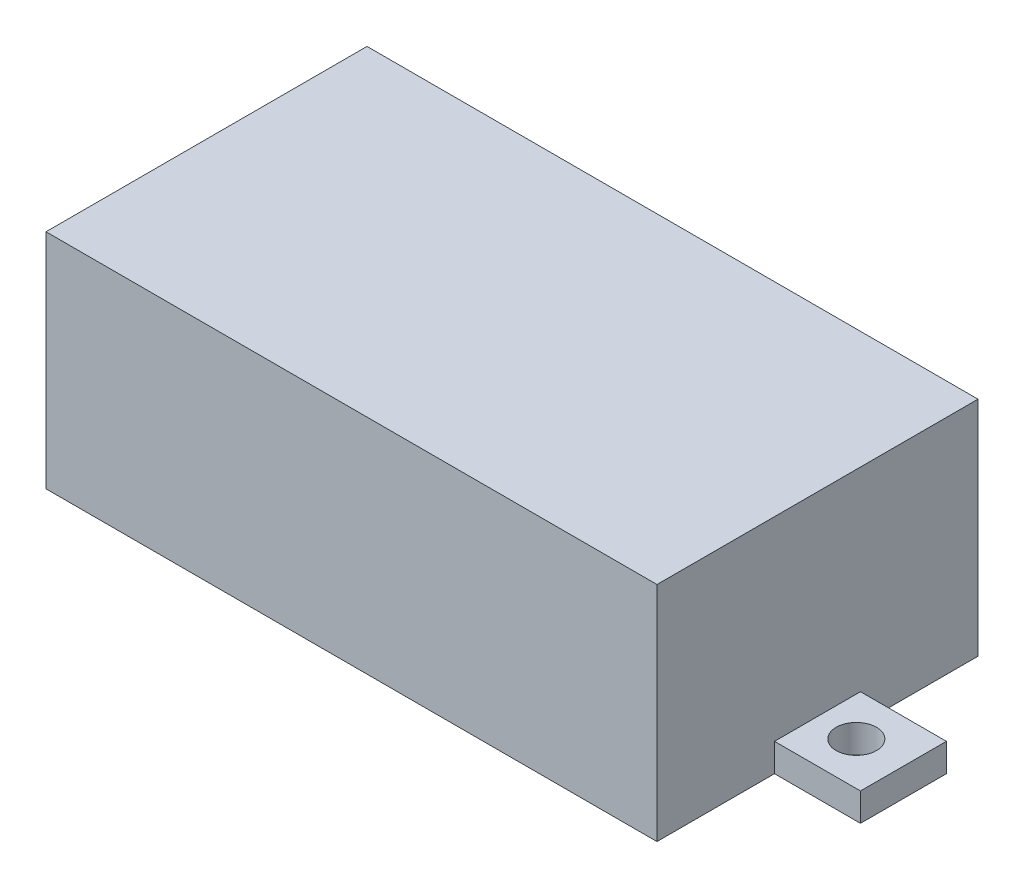
SolidWorks part; units mm, degrees
ref_plane "Front Plane" through (0, 0, 0) normal (0, 0, 1) x (1, 0, 0)
ref_plane "Top Plane" through (0, 0, 0) normal (0, 1, 0) x (1, 0, 0)
ref_plane "Right Plane" through (0, 0, 0) normal (1, 0, 0) x (0, 0, -1)
sketch "Sketch2" plane through (0, 0, 0) normal (0, 1, 0) x (1, 0, 0)
  line L1 (-29.5, -15.5) -> (29.5, -15.5)
  line L2 (-29.5, -15.5) -> (-29.5, 15.5)
  line L3 (-29.5, 15.5) -> (29.5, 15.5)
  line L4 (29.5, -15.5) -> (29.5, 15.5)
  line L5 (-29.5, -15.5) -> (29.5, 15.5) construction
  line L6 (-29.5, 15.5) -> (29.5, -15.5) construction
  point P0 (0, 0)
  dimension "D1" = 31
  dimension "D2" = 59
extrude "Boss-Extrude1" add sketch "Sketch2" along normal blind 21.5
sketch "Sketch3" plane through (0, 0, 0) normal (0, -1, 0) x (1, 0, 0)
  line L0 (-33.25, 0) -> (33.25, 0) construction
  line L1 (-29.5, -15.5) -> (-29.5, 15.5) construction
  line L2 (-29.5, -4.15) -> (-37.8, -4.15)
  line L3 (-29.5, -4.15) -> (-29.5, 4.15)
  line L4 (-29.5, 4.15) -> (-37.8, 4.15)
  line L5 (-37.8, -4.15) -> (-37.8, 4.15)
  line L6 (0, -15.5) -> (0, 15.5) construction
  line L7 (29.5, -15.5) -> (-29.5, -15.5) construction
  line L8 (-29.5, 15.5) -> (29.5, 15.5) construction
  line L9 (29.5, 4.15) -> (37.8, 4.15)
  line L10 (37.8, -4.15) -> (37.8, 4.15)
  line L11 (29.5, -4.15) -> (37.8, -4.15)
  line L12 (29.5, -4.15) -> (29.5, 4.15)
  circle A0 centre (-33.25, 0) radius 1.95
  circle A1 centre (33.25, 0) radius 1.95
  point P4 (0, 0)
  point P11 (-29.5, 0)
  dimension "D4" = 3.9
  dimension "D1" = 66.5
  dimension "D2" = 8.3
  dimension "D3" = 8.3
extrude "Boss-Extrude2" add sketch "Sketch3" against normal blind 2.71
